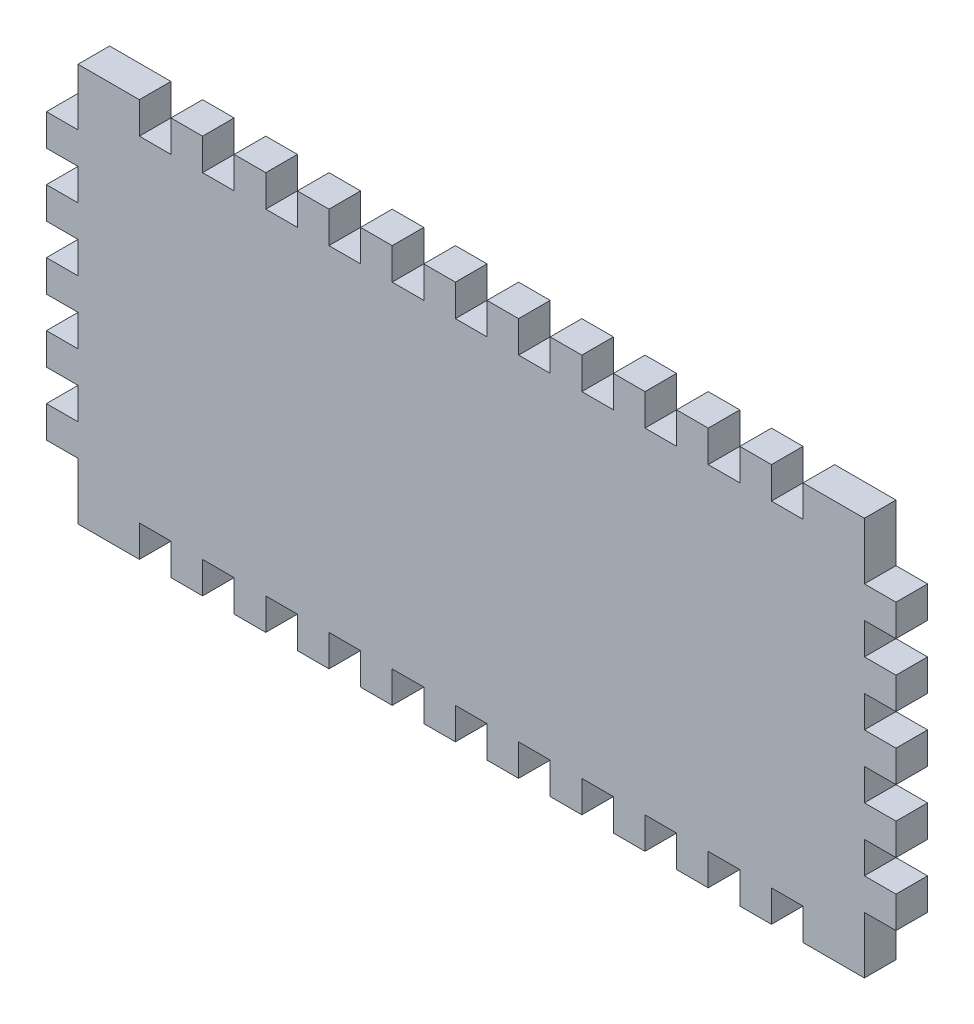
SolidWorks part; units mm, degrees
ref_plane "Front Plane" through (0, 0, 0) normal (0, 0, 1) x (1, 0, 0)
ref_plane "Top Plane" through (0, 0, 0) normal (0, 1, 0) x (1, 0, 0)
ref_plane "Right Plane" through (0, 0, 0) normal (1, 0, 0) x (0, 0, -1)
sketch "Sketch1" plane through (0, 0, 0) normal (0, 0, 1) x (1, 0, 0)
  line L1 (39.5, -20) -> (-39.5, -20)
  line L2 (39.5, -20) -> (39.5, 20)
  line L3 (39.5, 20) -> (-39.5, 20)
  line L4 (-39.5, -20) -> (-39.5, 20)
  line L5 (39.5, -20) -> (-39.5, 20) construction
  line L6 (39.5, 20) -> (-39.5, -20) construction
  point P0 (0, 0)
  dimension "D1" = 40
  dimension "D2" = 79
extrude "Boss-Extrude1" add sketch "Sketch1" along normal blind 3.175
sketch "Sketch2" plane through (0, 0, 3.175) normal (0, 0, 1) x (1, 0, 0)
  line L0 (-39.5, -20) -> (39.5, -20) construction
  line L1 (-1.5875, -16.825) -> (1.5875, -16.825)
  line L2 (-1.5875, -16.825) -> (-1.5875, -23.175)
  line L3 (-1.5875, -23.175) -> (1.5875, -23.175)
  line L4 (1.5875, -16.825) -> (1.5875, -23.175)
  line L5 (-1.5875, -16.825) -> (1.5875, -23.175) construction
  line L6 (-1.5875, -23.175) -> (1.5875, -16.825) construction
  point P0 (0, -20)
  dimension "D1" = 6.35
  dimension "D2" = 3.175
extrude "Cut-Extrude1" cut sketch "Sketch2" against normal blind 10
mirror "Mirror1" about plane through (0, 0, 0) normal (0, 1, 0) of "Cut-Extrude1"
pattern_linear "LPattern1" count 6 spacing 6.35 along (1, 0, 0) count 6 spacing 6.35 along (-1, 0, 0) of "Mirror1", "Cut-Extrude1"
sketch "Sketch3" plane through (0, 0, 3.175) normal (0, 0, 1) x (1, 0, 0)
  line L0 (-39.5, 20) -> (-39.5, -20) construction
  line L1 (-36.325, -1.5875) -> (-42.675, -1.5875)
  line L2 (-36.325, -1.5875) -> (-36.325, 1.5875)
  line L3 (-36.325, 1.5875) -> (-42.675, 1.5875)
  line L4 (-42.675, -1.5875) -> (-42.675, 1.5875)
  line L5 (-36.325, -1.5875) -> (-42.675, 1.5875) construction
  line L6 (-36.325, 1.5875) -> (-42.675, -1.5875) construction
  point P0 (-39.5, 0)
  dimension "D1" = 6.35
  dimension "D2" = 3.175
extrude "Boss-Extrude2" add sketch "Sketch3" against normal up to surface (3.175 mm away) up to face at (0, 0, 0)
pattern_linear "LPattern2" count 3 spacing 6.35 along (0, 1, 0) count 3 spacing 6.35 along (0, -1, 0) of "Boss-Extrude2"
mirror "Mirror2" about plane through (0, 0, 0) normal (1, 0, 0) of "LPattern2", "Boss-Extrude2"
